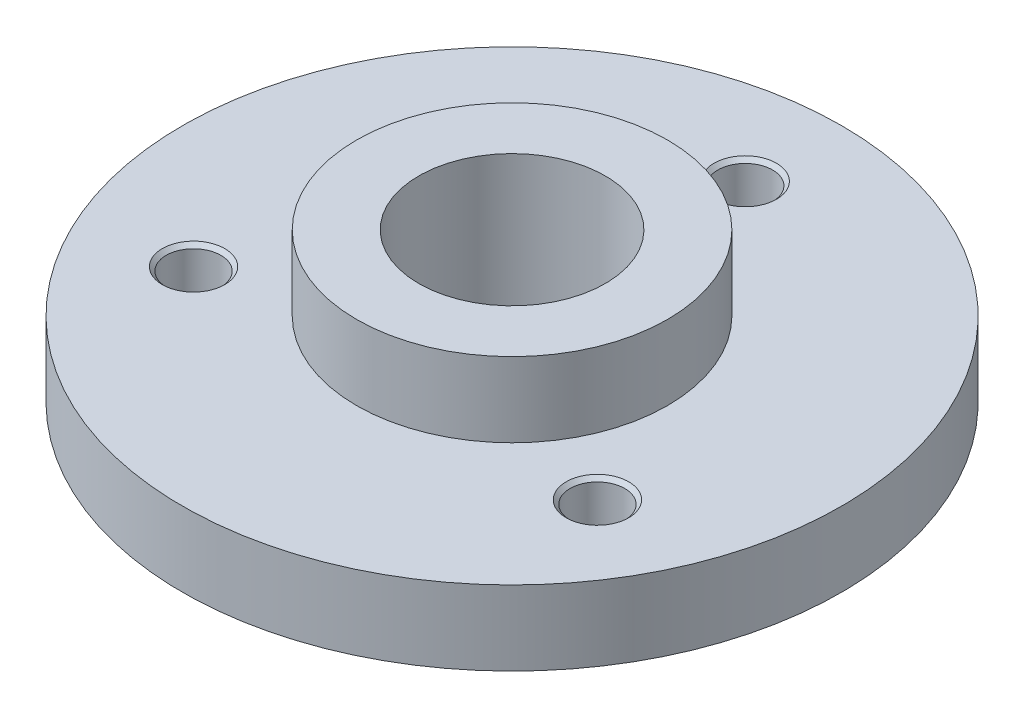
SolidWorks part; units mm, degrees
ref_plane "Front Plane" through (0, 0, 0) normal (0, 0, 1) x (1, 0, 0)
ref_plane "Top Plane" through (0, 0, 0) normal (0, 1, 0) x (1, 0, 0)
ref_plane "Right Plane" through (0, 0, 0) normal (1, 0, 0) x (0, 0, -1)
sketch "Sketch1" plane through (0, 0, 0) normal (1, 0, 0) x (0, 0, -1)
  line L0 (0, 0) -> (0, 24)
  line L1 (0, 24) -> (25, 24)
  line L2 (25, 24) -> (25, 12)
  line L3 (25, 12) -> (53, 12)
  line L4 (53, 12) -> (53, 0)
  line L5 (53, 0) -> (0, 0)
  dimension "D1" = 53
  dimension "D2" = 25
  dimension "D3" = 12
  dimension "D4" = 24
revolve "Revolve1" add sketch "Sketch1" angle 360 about L0
hole_wizard "Hole1" positions "Sketch2" profile "Sketch3" legacy end condition through all
sketch "Sketch2" plane through (0, 24, 0) normal (0, 1, 0) x (1, 0, 0)
  point P0 (0, 0)
sketch "Sketch3" plane through (0, 24, 0) normal (1, 0, 0) x (0, 0, 1)
  line L0 (0, 0) -> (0, 24)
  line L1 (0, 24) -> (15, 24)
  line L2 (15, 24) -> (15, 0)
  line L3 (15, 0) -> (0, 0)
  line L4 (0, 110) -> (0, -10) construction
  dimension "Diameter" = 30
  dimension "Depth" = 24
hole_wizard "M10x1.25 Tapped Hole1" positions "Sketch4" profile "Sketch5" tap size "M10x1.25" standard "ANSI Metric" end condition through all
sketch "Sketch4" plane through (0, 12, 0) normal (0, 1, 0) x (1, 0, 0)
  point P0 (0, 37.5)
  dimension "D1" = 37.5
sketch "Sketch5" plane through (0, 12, -37.5) normal (1, 0, 0) x (0, 0, 1)
  line L0 (0, 0) -> (0, 12)
  line L1 (0, 12) -> (4.4, 12)
  line L2 (4.4, 12) -> (4.4, 0.625)
  line L3 (4.4, 0.625) -> (5.025, 0)
  line L5 (5.025, 0) -> (0, 0)
  line L6 (-4.4, 0.625) -> (-5.025, 0) construction
  line L11 (0, -6.35) -> (0, 107.95) construction
  dimension "Thru Tap Drill Dia." = 8.8
  dimension "Thru Tap Drill Depth" = 12
  dimension "Near C'Sink Dia." = 10.05
  dimension "Near C'Sink Angle" = 90
cosmetic thread "Hole Thread1" parameters "D2"=10
pattern_circular "CirPattern1" count 3 over 360 about axis through (0, 0, 0) along (0, 1, 0) of "M10x1.25 Tapped Hole1"
cosmetic thread "Hole Thread2"
cosmetic thread "Hole Thread3"
